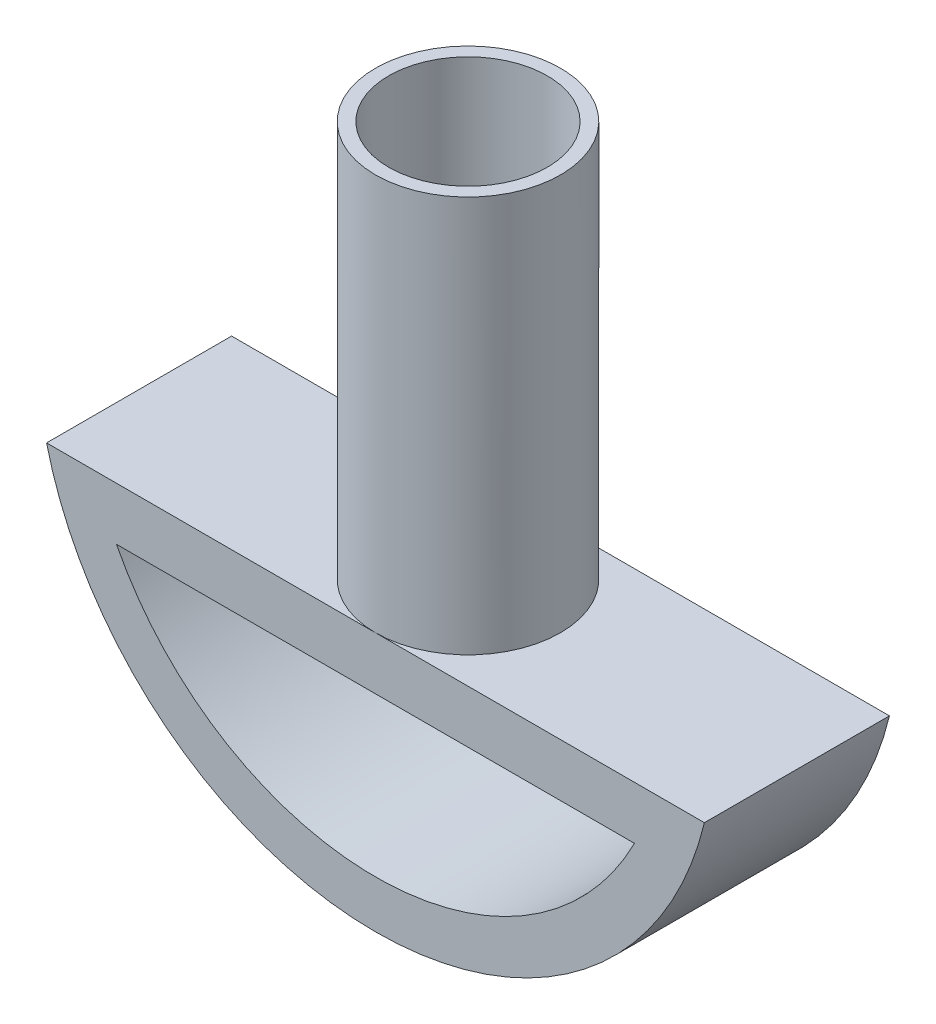
SolidWorks part; units mm, degrees
ref_plane "Ön Düzlem" through (0, 0, 0) normal (0, 0, 1) x (1, 0, 0)
ref_plane "Üst Düzlem" through (0, 0, 0) normal (0, 1, 0) x (1, 0, 0)
ref_plane "Sağ Düzlem" through (0, 0, 0) normal (1, 0, 0) x (0, 0, -1)
sketch "Çizim1" plane through (0, 0, 0) normal (0, 0, 1) x (1, 0, 0)
  line L3 (-62.2174, -15) -> (62.2174, -15)
  arc A0 (-62.2174, -15) -> (62.2174, -15) centre (0, 0) ccw
  dimension "D1" = 128
  dimension "D2" = 15
extrude "Yükseklik-Ekstrüzyon1" add sketch "Çizim1" along normal blind 35
sketch "Çizim2" plane through (0, 0, 35) normal (0, 0, 1) x (1, 0, 0)
  line L0 (62.2174, -15) -> (-62.2174, -15) construction
  line L3 (-48.9898, -25) -> (48.9898, -25)
  arc A0 (-48.9898, -25) -> (48.9898, -25) centre (0, 0) ccw
  dimension "D1" = 110
  dimension "D2" = 10
extrude "Kes-Ekstrüzyon1" cut sketch "Çizim2" against normal blind 35
sketch "Çizim3" plane through (0, -15, 0) normal (0, 1, 0) x (1, 0, 0)
  circle A0 centre (0, -17.5) radius 17.5
  circle A1 centre (0, -17.5) radius 15
  dimension "D1" = 30
extrude "Yükseklik-Ekstrüzyon2" add sketch "Çizim3" along normal blind 75
sketch "Çizim4" plane through (0, -15, 0) normal (0, 1, 0) x (1, 0, 0)
  circle A0 centre (0, -17.5) radius 7.5
  dimension "D1" = 15
extrude "Kes-Ekstrüzyon2" cut sketch "Çizim4" against normal blind 28
